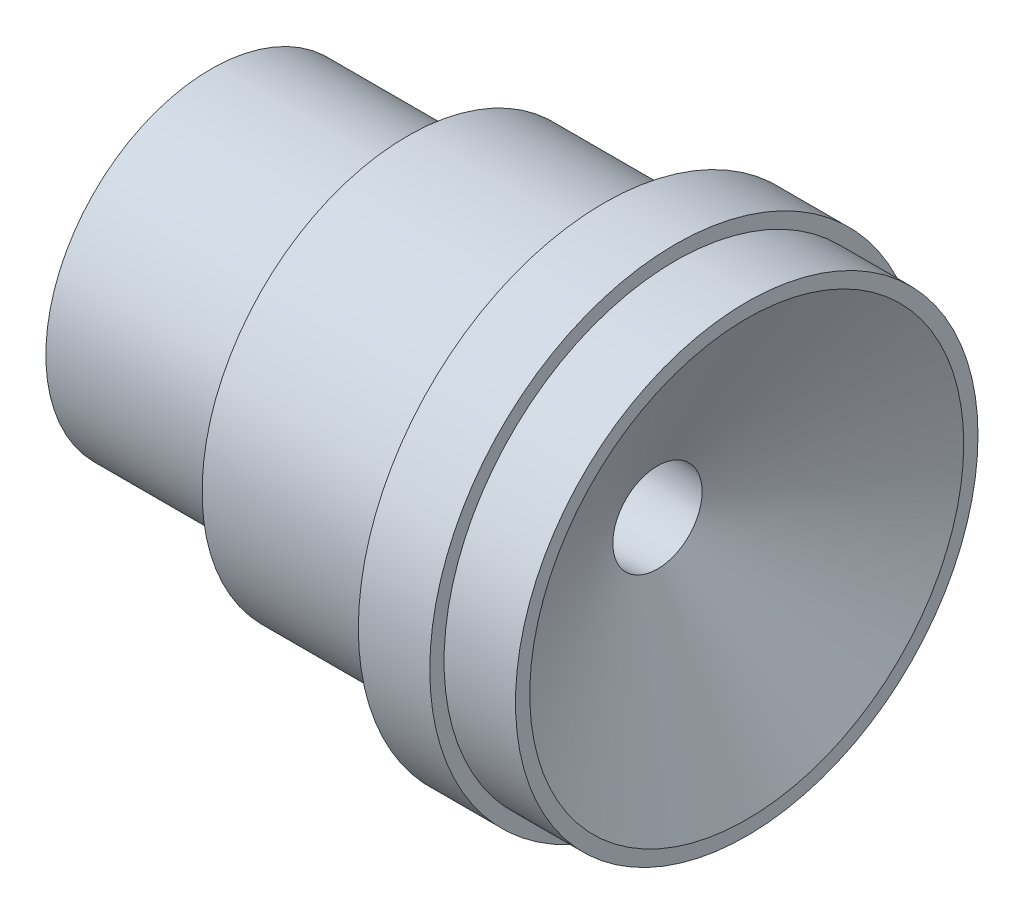
SolidWorks part; units mm, degrees
material "POLYURETHANE (11671)"
ref_plane "Front Plane" through (0, 0, 0) normal (0, 0, 1) x (1, 0, 0)
ref_plane "Top Plane" through (0, 0, 0) normal (0, 1, 0) x (1, 0, 0)
ref_plane "Right Plane" through (0, 0, 0) normal (1, 0, 0) x (0, 0, -1)
sketch "Sketch1" plane through (0, 0, 0) normal (0, 0, 1) x (1, 0, 0)
  line L0 (0, 6.35) -> (12.7, 30.861)
  line L1 (12.7, 30.861) -> (12.7, 32.893)
  line L2 (12.7, 32.893) -> (2.54, 32.893)
  line L3 (2.54, 32.893) -> (2.54, 34.925)
  line L4 (2.54, 34.925) -> (-7.62, 34.925)
  line L5 (-7.62, 34.925) -> (-7.62, 29.21)
  line L6 (-7.62, 29.21) -> (-35.56, 29.21)
  line L7 (-35.56, 29.21) -> (-35.56, 23.495)
  line L8 (-35.56, 23.495) -> (-63.5, 23.495)
  line L9 (-63.5, 23.495) -> (-63.5, 10.795)
  line L10 (-63.5, 10.795) -> (0, 6.35)
  line L11 (0, 0) -> (-50000, 0)
  dimension "D1" = 34.925
  dimension "D2" = 2.032
  dimension "D3" = 2.032
  dimension "D4" = 6.35
  dimension "D5" = 10.16
  dimension "D6" = 76.2
  dimension "D7" = 12.7
  dimension "D8" = 12.7
  dimension "D9" = 11.43
revolve "Revolve1" add sketch "Sketch1" angle 360 about L11
